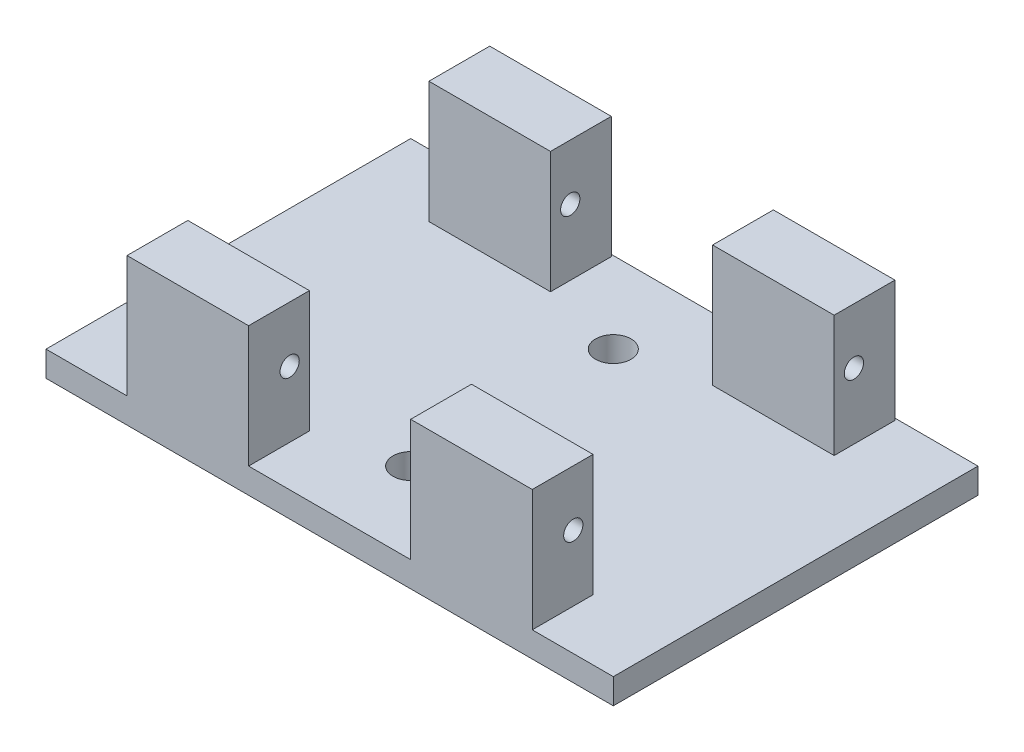
SolidWorks part; units mm, degrees
ref_plane "前视基准面" through (0, 0, 0) normal (0, 0, 1) x (1, 0, 0)
ref_plane "上视基准面" through (0, 0, 0) normal (0, 1, 0) x (1, 0, 0)
ref_plane "右视基准面" through (0, 0, 0) normal (1, 0, 0) x (0, 0, -1)
other "Configuration Table"
sketch "草图1" plane through (0, 0, 0) normal (0, 1, 0) x (1, 0, 0)
  line L1 (-28, 18) -> (28, 18)
  line L2 (-28, 18) -> (-28, -18)
  line L3 (-28, -18) -> (28, -18)
  line L4 (28, 18) -> (28, -18)
  line L5 (-28, 18) -> (28, -18) construction
  line L6 (-28, -18) -> (28, 18) construction
  point P0 (0, 0)
  dimension "D1" = 56
  dimension "D2" = 36
extrude "凸台-拉伸1" add sketch "草图1" along normal blind 2.5
sketch "草图2" plane through (0, 2.5, 0) normal (0, 1, 0) x (1, 0, 0)
  line L0 (-28, -18) -> (28, -18) construction
  line L1 (8, 17.8) -> (20, 17.8)
  line L2 (8, 17.8) -> (8, 11.8)
  line L3 (8, 11.8) -> (20, 11.8)
  line L4 (20, 17.8) -> (20, 11.8)
  line L5 (8, -12) -> (20, -12)
  line L6 (8, -12) -> (8, -18)
  line L7 (8, -18) -> (20, -18)
  line L8 (20, -12) -> (20, -18)
  line L9 (28, -18) -> (28, 18) construction
  dimension "D1" = 23.8
  dimension "D2" = 6
  dimension "D3" = 6
  dimension "D4" = 12
  dimension "D5" = 8
extrude "凸台-拉伸2" add sketch "草图2" along normal blind 12
sketch "草图3" plane through (20, 0, 0) normal (1, 0, 0) x (0, 0, -1)
  line L0 (-18, 2.5) -> (18, 2.5) construction
  line L1 (11.8, 2.5) -> (17.8, 2.5) construction
  line L2 (-12, 14.5) -> (-12, 2.5) construction
  line L3 (11.8, 14.5) -> (11.8, 2.5) construction
  circle A0 centre (-13.95, 9) radius 0.95
  circle A1 centre (13.75, 9) radius 0.95
  dimension "D1" = 6.5
  dimension "D2" = 6.5
  dimension "D3" = 1.95
  dimension "D4" = 1.95
  dimension "D5" = 1.9
  dimension "D6" = 1.9
extrude "切除-拉伸1" cut sketch "草图3" against normal through all
mirror "镜向1" about plane through (0, 0, 0) normal (1, 0, 0) of "切除-拉伸1", "凸台-拉伸2"
sketch "草图4" plane through (0, 2.5, 0) normal (0, 1, 0) x (1, 0, 0)
  circle A0 centre (0, -10) radius 1.75
  circle A1 centre (0, 10) radius 1.75
  dimension "D1" = 20
  dimension "D2" = 3.5
  dimension "D3" = 3.5
  dimension "D4" = 10
extrude "切除-拉伸2" cut sketch "草图4" against normal through all
